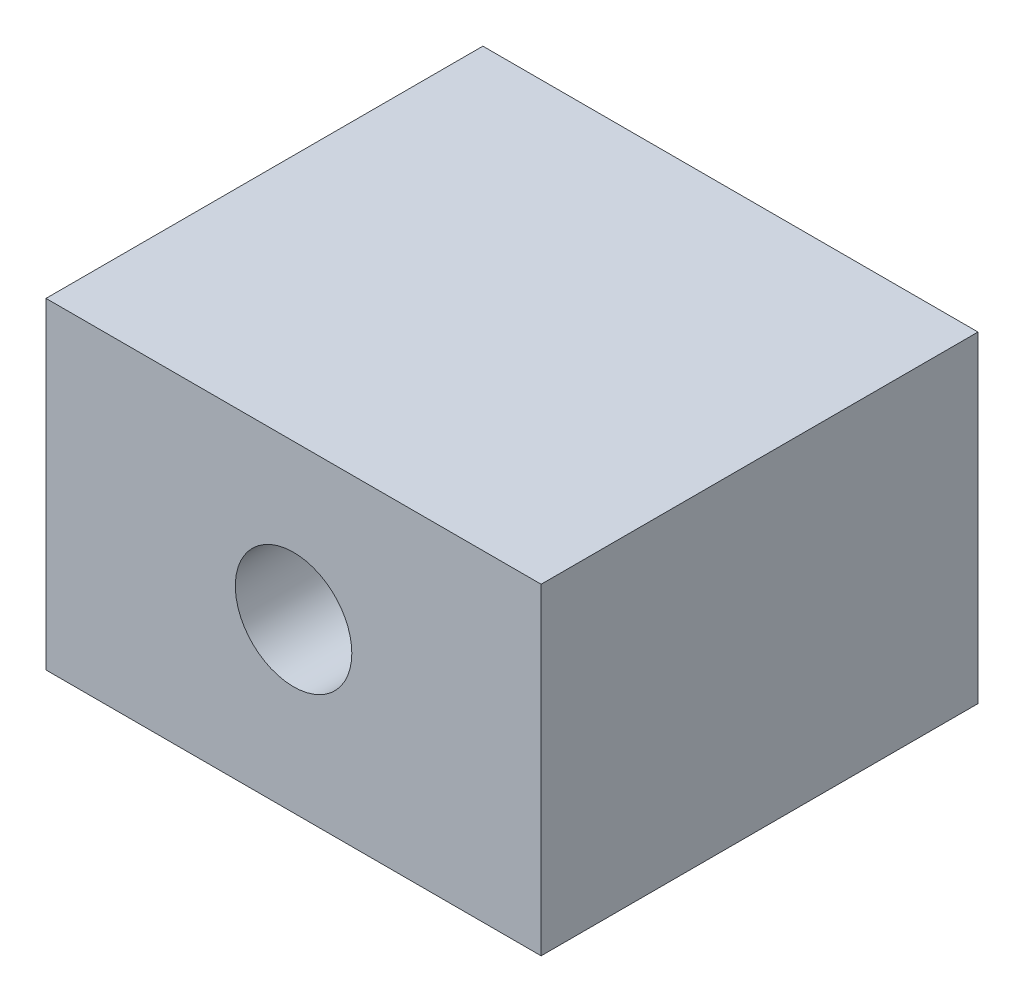
SolidWorks part; units mm, degrees
ref_plane "Front Plane" through (0, 0, 0) normal (0, 0, 1) x (1, 0, 0)
ref_plane "Top Plane" through (0, 0, 0) normal (0, 1, 0) x (1, 0, 0)
ref_plane "Right Plane" through (0, 0, 0) normal (1, 0, 0) x (0, 0, -1)
sketch "Sketch1" plane through (0, 0, 0) normal (0, 0, 1) x (1, 0, 0)
  line L1 (0, 0) -> (34, 0)
  line L2 (0, 0) -> (0, 22.1)
  line L3 (0, 22.1) -> (34, 22.1)
  line L4 (34, 0) -> (34, 22.1)
  circle A0 centre (17, 11.5) radius 4
  dimension "D3" = 8
  dimension "D1" = 34
  dimension "D2" = 22.1
  dimension "D4" = 11.5
  dimension "D5" = 17
extrude "Boss-Extrude1" add sketch "Sketch1" along normal blind 30
